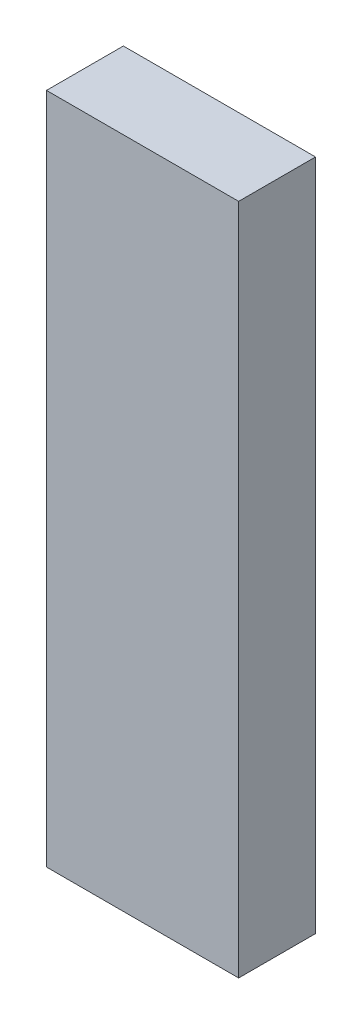
SolidWorks part; units mm, degrees
material "Oak"
ref_plane "Front Plane" through (0, 0, 0) normal (0, 0, 1) x (1, 0, 0)
ref_plane "Top Plane" through (0, 0, 0) normal (0, 1, 0) x (1, 0, 0)
ref_plane "Right Plane" through (0, 0, 0) normal (1, 0, 0) x (0, 0, -1)
sketch "Sketch1" plane through (0, 0, 0) normal (0, 1, 0) x (1, 0, 0)
  line L1 (-25.4, 10.16) -> (25.4, 10.16)
  line L2 (-25.4, 10.16) -> (-25.4, -10.16)
  line L3 (-25.4, -10.16) -> (25.4, -10.16)
  line L4 (25.4, 10.16) -> (25.4, -10.16)
  line L5 (-25.4, 10.16) -> (25.4, -10.16) construction
  line L6 (-25.4, -10.16) -> (25.4, 10.16) construction
  point P0 (0, 0)
  dimension "D1" = 50.8
  dimension "D2" = 20.32
extrude "Boss-Extrude1" add sketch "Sketch1" along normal blind 177.8 contours L1 L4 L3 L2
